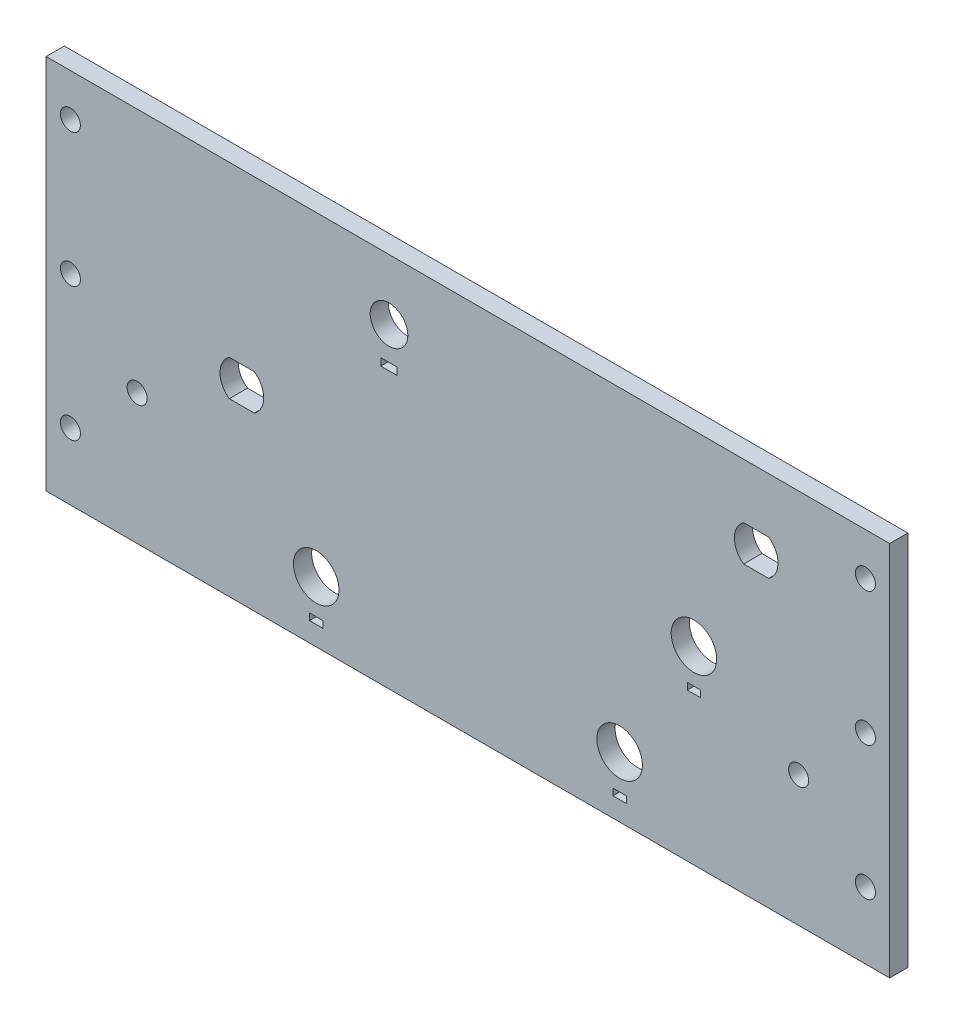
SolidWorks part; units mm, degrees
ref_plane "Front Plane" through (0, 0, 0) normal (0, 0, 1) x (1, 0, 0)
ref_plane "Top Plane" through (0, 0, 0) normal (0, 1, 0) x (1, 0, 0)
ref_plane "Right Plane" through (0, 0, 0) normal (1, 0, 0) x (0, 0, -1)
sketch "Sketch1" plane through (0, 0, 0) normal (0, 0, 1) x (1, 0, 0)
  line L0 (43.4, 3.2) -> (43.4, 4.3)
  line L1 (0, 0) -> (139, 0)
  line L2 (0, 0) -> (0, 62)
  line L3 (0, 62) -> (139, 62)
  line L4 (139, 0) -> (139, 62)
  line L5 (69.5, 62) -> (69.5, 0) construction
  line L17 (45.6, 3.2) -> (45.6, 4.3)
  line L18 (43.4, 4.3) -> (45.6, 4.3)
  line L19 (94.5, 10) -> (94.5, 0) construction
  line L20 (43.4, 3.2) -> (45.6, 3.2)
  line L21 (93.4, 3.2) -> (95.6, 3.2)
  line L22 (93.4, 3.2) -> (93.4, 4.3)
  line L23 (93.4, 4.3) -> (95.6, 4.3)
  line L24 (95.6, 3.2) -> (95.6, 4.3)
  line L25 (93.4, 3.2) -> (95.6, 4.3) construction
  line L26 (93.4, 4.3) -> (95.6, 3.2) construction
  line L27 (43.4, 4.3) -> (45.6, 3.2) construction
  line L28 (43.4, 3.2) -> (45.6, 4.3) construction
  line L33 (44.5, 10) -> (13.4787, 63.7305) construction
  line L34 (94.5, 10) -> (106.75, 31.2176) construction
  line L40 (106.75, 31.2176) -> (106.75, -31.4168) construction
  line L41 (105.65, 24.4176) -> (107.85, 24.4176)
  line L42 (105.65, 24.4176) -> (105.65, 25.5176)
  line L43 (105.65, 25.5176) -> (107.85, 25.5176)
  line L44 (107.85, 24.4176) -> (107.85, 25.5176)
  line L45 (105.65, 24.4176) -> (107.85, 25.5176) construction
  line L46 (105.65, 25.5176) -> (107.85, 24.4176) construction
  line L53 (56.5, 52) -> (56.5, 46) construction
  line L54 (55.15, 45.4) -> (57.85, 45.4)
  line L55 (55.15, 45.4) -> (55.15, 46.6)
  line L56 (55.15, 46.6) -> (57.85, 46.6)
  line L57 (57.85, 45.4) -> (57.85, 46.6)
  line L58 (55.15, 45.4) -> (57.85, 46.6) construction
  line L59 (55.15, 46.6) -> (57.85, 45.4) construction
  line L60 (114.9366, 47.05) -> (119.0634, 47.05)
  line L61 (119.0634, 52.95) -> (114.9366, 52.95)
  line L69 (30.1866, 28.2676) -> (34.3134, 28.2676)
  line L70 (34.3134, 34.1676) -> (30.1866, 34.1676)
  circle A2 centre (94.5, 10) radius 3.75
  circle A4 centre (4, 33) radius 1.65
  circle A5 centre (135, 33) radius 1.65
  circle A6 centre (135, 11) radius 1.65
  circle A7 centre (4, 11) radius 1.65
  circle A10 centre (106.75, 31.2176) radius 3.75
  circle A11 centre (124, 21.5) radius 1.65
  circle A12 centre (44.5, 10) radius 3.75
  circle A14 centre (15, 21.5) radius 1.65
  arc A15 (114.9366, 52.95) -> (114.9366, 47.05) centre (117, 50) ccw
  circle A16 centre (56.5, 52) radius 3.1
  circle A17 centre (4, 55) radius 1.65
  circle A18 centre (135, 55) radius 1.65
  arc A19 (119.0634, 47.05) -> (119.0634, 52.95) centre (117, 50) ccw
  arc A20 (30.1866, 34.1676) -> (30.1866, 28.2676) centre (32.25, 31.2176) ccw
  arc A21 (34.3134, 28.2676) -> (34.3134, 34.1676) centre (32.25, 31.2176) ccw
  point P41 (94.5, 3.75)
  point P52 (56.5, 46)
  point P55 (106.75, 24.9676)
  dimension "D3" = 2
  dimension "D5" = 12
  dimension "D8" = 3.3
  dimension "D24" = 7.5
  dimension "D25" = 10
  dimension "D34" = 7.5
  dimension "D43" = 7.2
  dimension "D16" = 3.6
  dimension "D37" = 6.2
  dimension "D1" = 139
  dimension "D2" = 62
  dimension "D6" = 60
  dimension "D7" = 50
  dimension "D11" = 131
  dimension "D12" = 4
  dimension "D13" = 29
  dimension "D14" = 22
  dimension "D15" = 11
  dimension "D17" = 24.5
  dimension "D18" = 5.9
  dimension "D19" = 22
  dimension "D20" = 4
  dimension "D21" = 2.2
  dimension "D22" = 1.1
  dimension "D23" = 5.7
  dimension "D26" = 25
  dimension "D27" = 10
  dimension "D29" = 21.5
  dimension "D30" = 15
  dimension "D31" = 15
  dimension "D32" = 2.2
  dimension "D33" = 1.1
  dimension "D35" = 5.7
  dimension "D36" = 60
  dimension "D38" = 2.7
  dimension "D39" = 1.2
  dimension "D40" = 6
  dimension "D41" = 7
  dimension "D42" = 4
  dimension "D44" = 5.9
  dimension "D45" = 13
  dimension "D9" = 2
  dimension "D10" = 2
extrude "Boss-Extrude1" add sketch "Sketch1" along normal blind 3
